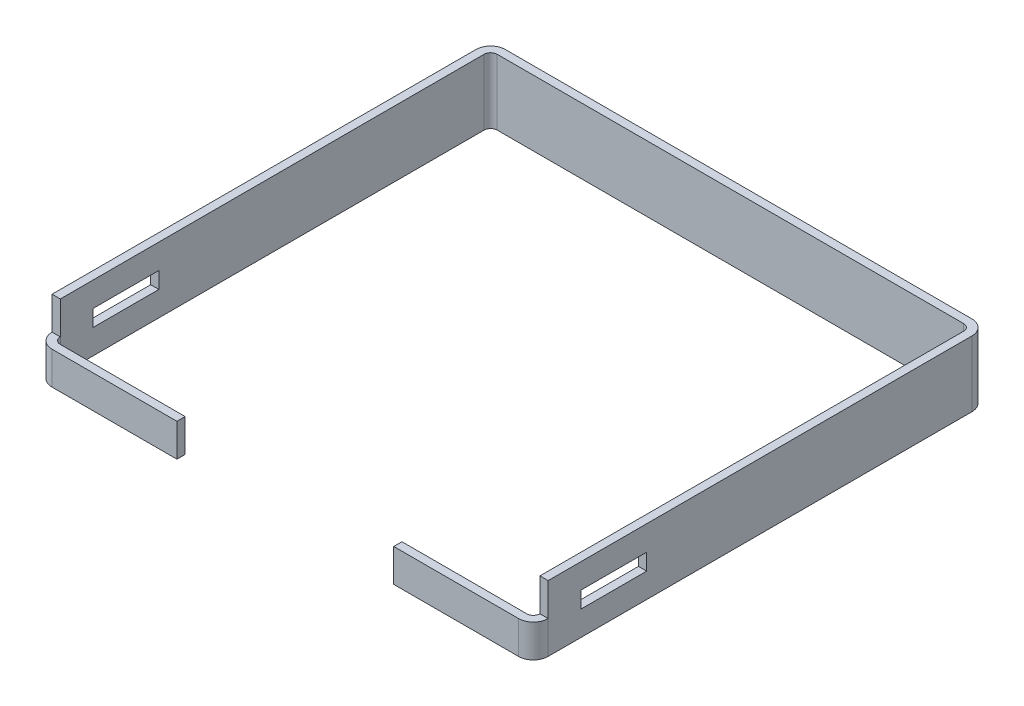
SolidWorks part; units mm, degrees
ref_plane "Front Plane" through (0, 0, 0) normal (0, 0, 1) x (1, 0, 0)
ref_plane "Top Plane" through (0, 0, 0) normal (0, 1, 0) x (1, 0, 0)
ref_plane "Right Plane" through (0, 0, 0) normal (1, 0, 0) x (0, 0, -1)
sketch "Sketch1" plane through (0, 0, 0) normal (0, 1, 0) x (1, 0, 0)
  line L0 (-92.71, 0) -> (92.71, 0)
  line L1 (-92.71, 0) -> (-92.71, -168.91)
  line L2 (92.71, 0) -> (92.71, -168.91)
  line L8 (-92.71, -168.91) -> (-41.91, -168.91)
  line L9 (92.71, -168.91) -> (41.91, -168.91)
  line L10 (-95.885, -172.085) -> (-41.91, -172.085)
  line L11 (-95.885, 3.175) -> (-95.885, -172.085)
  line L12 (-95.885, 3.175) -> (95.885, 3.175)
  line L13 (95.885, 3.175) -> (95.885, -172.085)
  line L14 (95.885, -172.085) -> (41.91, -172.085)
  line L15 (-41.91, -168.91) -> (-41.91, -172.085)
  line L16 (41.91, -168.91) -> (41.91, -172.085)
  point P3 (0, 0)
  dimension "D1" = 185.42
  dimension "D2" = 168.91
  dimension "D3" = 50.8
  dimension "D4" = 50.8
  dimension "D5" = 3.175
extrude "Boss-Extrude1" add sketch "Sketch1" along normal blind 25.4
fillet "Fillet1" radius 2.54 4 edges at (92.71, 12.7, 0) (-92.71, 12.7, 0) (92.71, 12.7, 168.91) (-92.71, 12.7, 168.91)
fillet "Fillet2" radius 5.715 4 edges at (-95.885, 12.7, 172.085) (95.885, 12.7, 172.085) (95.885, 12.7, -3.175) (-95.885, 12.7, -3.175)
sketch "Sketch2" plane through (0, 25.4, 0) normal (0, 1, 0) x (1, 0, 0)
  line L4 (-95.885, -172.085) -> (95.885, -172.085)
  line L5 (95.885, -172.085) -> (95.885, -166.37)
  line L6 (95.885, -166.37) -> (-95.885, -166.37)
  line L7 (-95.885, -166.37) -> (-95.885, -172.085)
extrude "Cut-Extrude1" cut sketch "Sketch2" against normal blind 12.7
sketch "Sketch3" plane through (-95.885, 0, 0) normal (-1, 0, 0) x (0, 0, 1)
  line L0 (128.27, 15.875) -> (128.27, 9.525)
  line L1 (128.27, 9.525) -> (153.67, 9.525)
  line L2 (153.67, 9.525) -> (153.67, 15.875)
  line L3 (153.67, 15.875) -> (128.27, 15.875)
  line L4 (166.37, 12.7) -> (166.37, 25.4) construction
  line L5 (2.54, 25.4) -> (166.37, 25.4) construction
  point P2 (140.97, 15.875)
  point P7 (153.67, 12.7)
  dimension "D1" = 25.4
  dimension "D2" = 12.7
  dimension "D3" = 6.35
  dimension "D4" = 25.4
extrude "Cut-Extrude2" cut sketch "Sketch3" against normal up to surface (191.77 mm away) up to face at (95.885, 12.7, 100.838)
